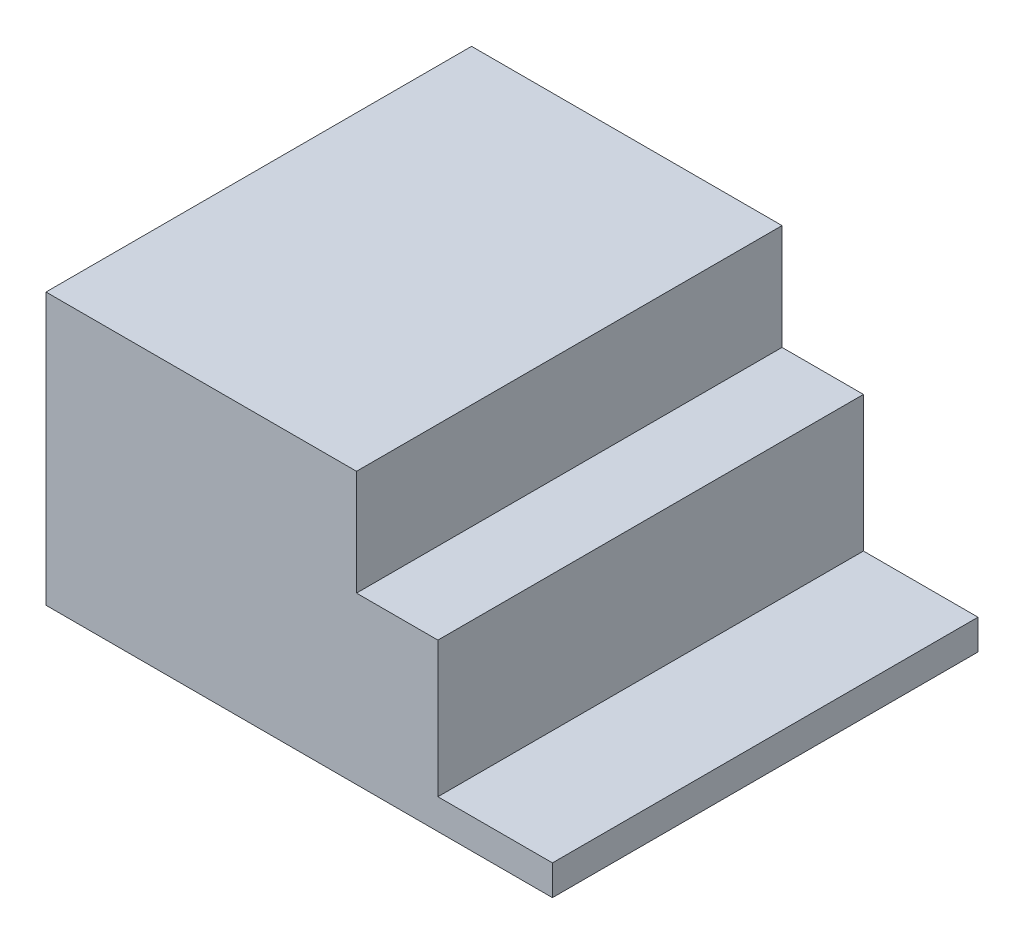
SolidWorks part; units mm, degrees
ref_plane "Front Plane" through (0, 0, 0) normal (0, 0, 1) x (1, 0, 0)
ref_plane "Top Plane" through (0, 0, 0) normal (0, 1, 0) x (1, 0, 0)
ref_plane "Right Plane" through (0, 0, 0) normal (1, 0, 0) x (0, 0, -1)
sketch "Sketch1" plane through (0, 0, 0) normal (0, 1, 0) x (1, 0, 0)
  line L1 (125, -70.5826) -> (-43, -70.5826)
  line L2 (125, -70.5826) -> (125, 70.5826)
  line L3 (125, 70.5826) -> (-43, 70.5826)
  line L4 (-43, -70.5826) -> (-43, 70.5826)
extrude "Boss-Extrude1" add sketch "Sketch1" along normal blind 90 contours L4 L3 L2 L1
sketch "Sketch2" plane through (0, 0, 0) normal (0, 0, 1) x (1, 0, 0)
  line L0 (125, 0) -> (-43, 0) construction
  line L1 (125, 90) -> (125, 0) construction
  line L2 (125, 10) -> (87, 10)
  line L3 (87, 10) -> (87, 55)
  line L4 (87, 55) -> (60, 55)
  line L5 (60, 55) -> (60, 90)
  line L6 (125, 90) -> (-43, 90) construction
  line L7 (60, 90) -> (125, 90)
  line L8 (125, 90) -> (125, 10)
  dimension "D1" = 10
  dimension "D2" = 38
  dimension "D3" = 45
  dimension "D4" = 27
extrude "Cut-Extrude1" cut sketch "Sketch2" against normal through all both and the other way through all contours L8 L7 L5 L4 L3 L2
